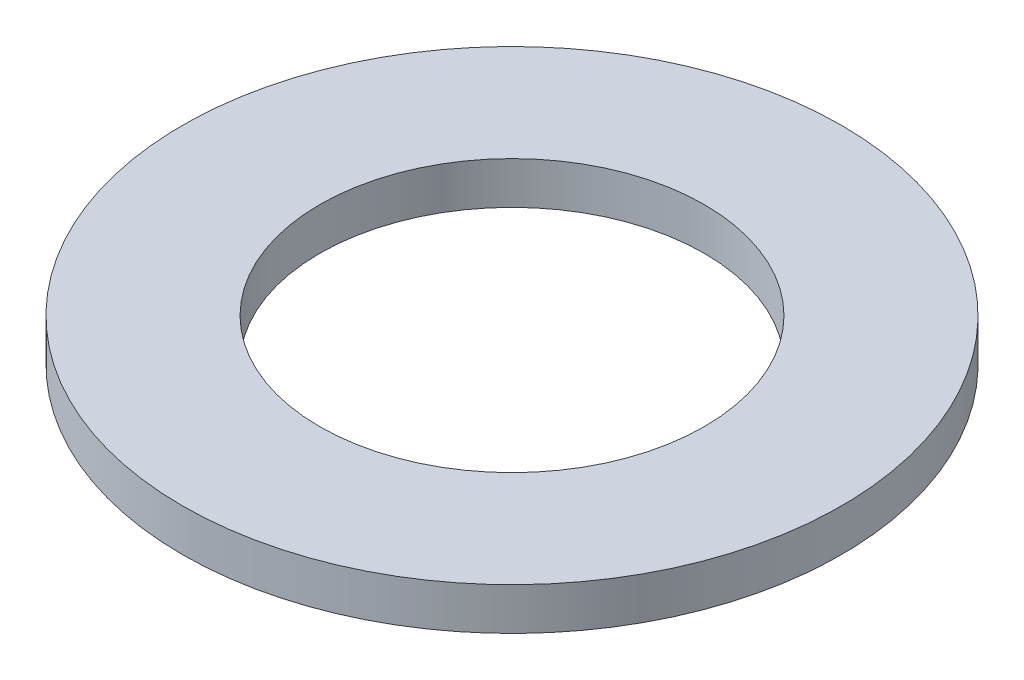
SolidWorks part; units mm, degrees
ref_plane "Front Plane" through (0, 0, 0) normal (0, 0, 1) x (1, 0, 0)
ref_plane "Top Plane" through (0, 0, 0) normal (0, 1, 0) x (1, 0, 0)
ref_plane "Right Plane" through (0, 0, 0) normal (1, 0, 0) x (0, 0, -1)
sketch "Sketch1" plane through (0, 0, 0) normal (0, 1, 0) x (1, 0, 0)
  circle A0 centre (0, 0) radius 49.53
  circle A1 centre (0, 0) radius 28.9052
  dimension "D1" = 57.8104
  dimension "D2" = 99.06
extrude "Boss-Extrude1" add sketch "Sketch1" along normal blind 6.35
